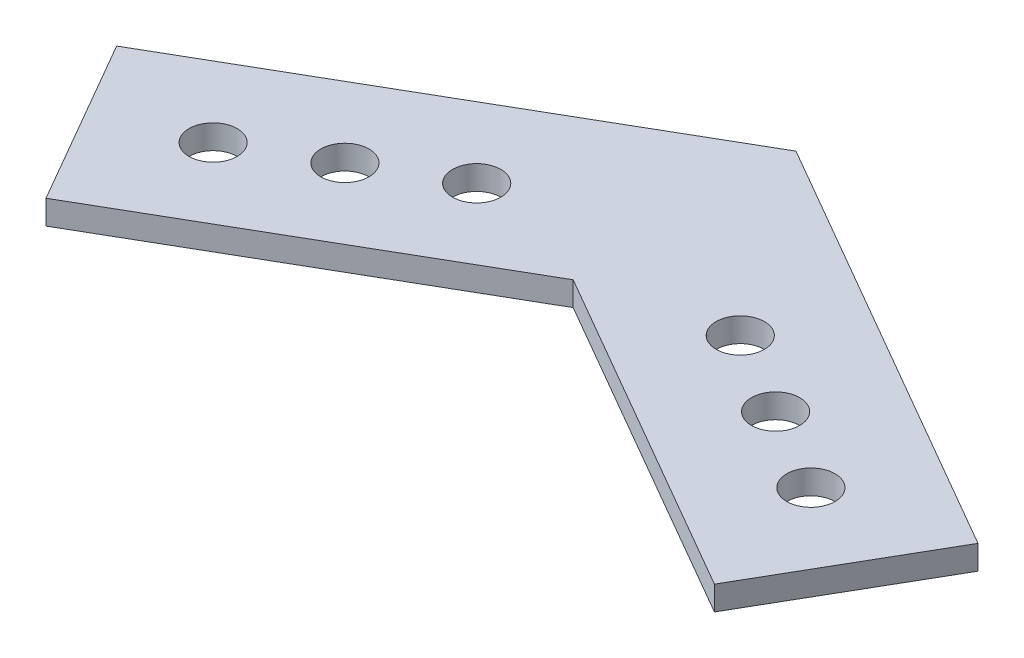
SolidWorks part; units mm, degrees
material "5052-H32"
ref_plane "Front Plane" through (0, 0, 0) normal (0, 0, 1) x (1, 0, 0)
ref_plane "Top Plane" through (0, 0, 0) normal (0, 1, 0) x (1, 0, 0)
ref_plane "Right Plane" through (0, 0, 0) normal (1, 0, 0) x (0, 0, -1)
sketch "Sketch1" plane through (0, 0, 0) normal (0, 1, 0) x (1, 0, 0)
  line L0 (-25.4, 14.6647) -> (0, 29.3294)
  line L5 (43.9941, -25.4) -> (0, 0)
  line L6 (43.9941, -25.4) -> (56.6941, -3.403)
  line L7 (56.6941, -3.403) -> (25.4, 14.6647)
  line L9 (0, 0) -> (-43.9941, -25.4)
  line L11 (-25.4, 14.6647) -> (-56.6941, -3.403)
  line L12 (-43.9941, -25.4) -> (-56.6941, -3.403)
  line L13 (0, 29.3294) -> (25.4, 14.6647)
  line L14 (-25.4, 14.6647) -> (0, 0) construction
  line L15 (25.4, 14.6647) -> (0, 0) construction
  line L16 (0, 0) -> (0, 29.3294) construction
  dimension "D1" = 25.4
  dimension "D2" = 25.4
  dimension "D5" = 120
  dimension "D3" = 50.8
  dimension "D4" = 50.8
extrude "Boss-Extrude1" add sketch "Sketch1" along normal blind 3.175 contours L0 L13 L7 L6 L5 L9 L12 L11
sketch "Sketch2" plane through (0, 3.175, 0) normal (0, 1, 0) x (1, 0, 0)
  line L0 (-56.6941, -3.403) -> (-43.9941, -25.4) construction
  line L1 (-39.3456, -8.0515) -> (-50.3441, -14.4015) construction
  line L2 (56.6941, -3.403) -> (43.9941, -25.4) construction
  line L3 (39.3456, -8.0515) -> (50.3441, -14.4015) construction
  circle A0 centre (-39.3456, -8.0515) radius 3.175
  circle A1 centre (39.3456, -8.0515) radius 3.175
  dimension "D1" = 6.35
  dimension "D2" = 12.7
sketch "Sketch7" plane through (0, 3.175, 0) normal (0, 1, 0) x (1, 0, 0)
  line L0 (-56.6941, -3.403) -> (-43.9941, -25.4) construction
  line L1 (-39.3456, -8.0515) -> (-50.3441, -14.4015) construction
  line L2 (56.6941, -3.403) -> (43.9941, -25.4) construction
  line L3 (39.3456, -8.0515) -> (50.3441, -14.4015) construction
  circle A0 centre (-39.3456, -8.0515) radius 3.175
  circle A1 centre (39.3456, -8.0515) radius 3.175
  dimension "D1" = 6.35
  dimension "D2" = 12.7
extrude "Cut-Extrude2" cut sketch "Sketch2" against normal blind 3.175 contours A0
pattern_linear "LPattern5" count 3 spacing 12.7 along (0.866, 0, -0.5) of "Cut-Extrude2"
extrude "Cut-Extrude3" cut sketch "Sketch7" against normal blind 3.175 contours A1
pattern_linear "LPattern6" count 3 spacing 12.7 along (-0.866, 0, -0.5) of "Cut-Extrude3"
equation "\"InnerAngle\"= 120"
equation "\"StockThickness\"= .125in"
equation "\"HoleDiameter\"= .25in"
equation "\"BarWidth\"= 1in"
equation "\"HoleSpacing\"= .5"
equation "\"AdditionalHoleCount\"= 3"
equation "\"D1@Sketch1\"=\"BarWidth\""
equation "\"D2@Sketch1\"= \"BarWidth\""
equation "\"WingLength\"= ( \"AdditionalHoleCount\" + 1 ) * \"HoleSpacing\""
equation "\"D5@Sketch1\"=\"InnerAngle\""
equation "\"D1@Boss-Extrude1\"=\"StockThickness\""
equation "\"D1@Sketch2\"=\"HoleDiameter\""
equation "\"D2@Sketch2\"=\"HoleSpacing\""
equation "\"D3@LPattern5\"=\"HoleSpacing\""
equation "\"D1@LPattern5\"=\"AdditionalHoleCount\""
equation "\"D2@Sketch7\"=\"HoleSpacing\""
equation "\"D1@Sketch7\"=\"HoleDiameter\""
equation "\"D3@LPattern6\"=\"HoleSpacing\""
equation "\"D1@LPattern6\"=\"AdditionalHoleCount\""
equation "\"D3@Sketch1\"=\"WingLength\""
equation "\"D4@Sketch1\"=\"WingLength\""
